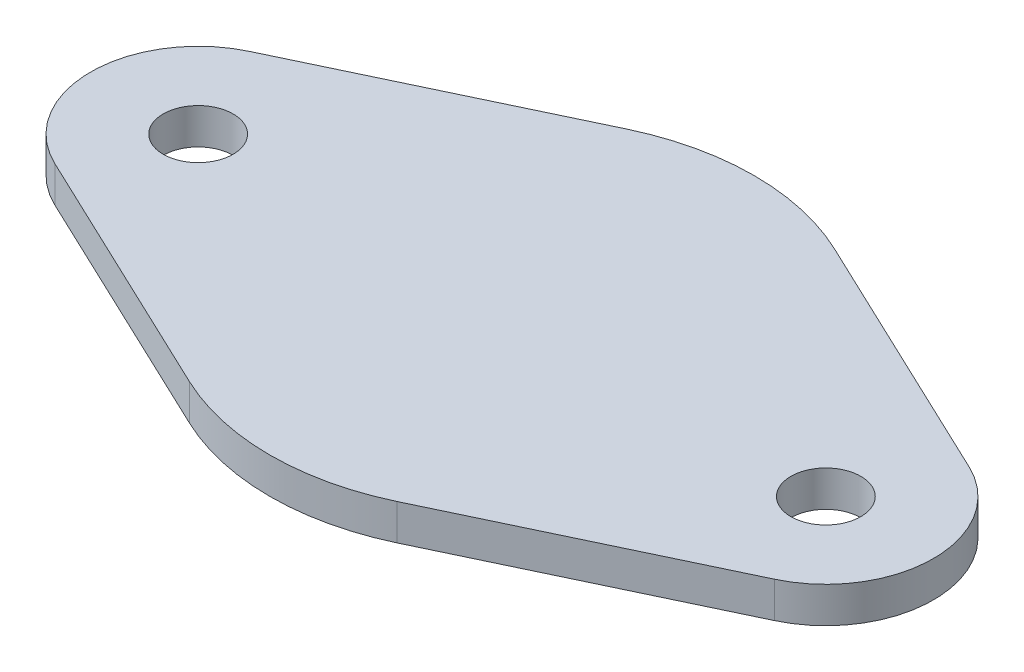
SolidWorks part; units mm, degrees
material "Thornel Mat VMA"
ref_plane "前视基准面" through (0, 0, 0) normal (0, 0, 1) x (1, 0, 0)
ref_plane "上视基准面" through (0, 0, 0) normal (0, 1, 0) x (1, 0, 0)
ref_plane "右视基准面" through (0, 0, 0) normal (1, 0, 0) x (0, 0, -1)
other "Configuration Table"
sketch "草图1" plane through (0, 0, 0) normal (0, 1, 0) x (1, 0, 0)
  line L0 (-40.5759, 0) -> (40.5265, 0) construction
  line L1 (0, 33.3733) -> (0, -29.1801) construction
  line L2 (-20.0714, 5.421) -> (-5.7857, 12.1974)
  line L3 (20.0714, 5.421) -> (5.7857, 12.1974)
  line L4 (20.0714, -5.421) -> (5.7857, -12.1974)
  line L5 (-20.0714, -5.421) -> (-5.7857, -12.1974)
  circle A0 centre (0, 0) radius 13.5 construction
  circle A1 centre (-17.5, 0) radius 1.95
  circle A2 centre (17.5, 0) radius 1.95
  arc A3 (-20.0714, 5.421) -> (-19.5517, -5.6383) centre (-17.5, 0) ccw
  arc A4 (20.0714, 5.421) -> (19.5517, -5.6383) centre (17.5, 0) cw
  arc A5 (5.7857, 12.1974) -> (-5.7857, 12.1974) centre (0, 0) ccw
  arc A6 (-5.7857, -12.1974) -> (5.7857, -12.1974) centre (0, 0) ccw
  point P17 (0, 0)
  point P23 (5.7675, -12.206)
  dimension "D1" = 27
  dimension "D2" = 35
  dimension "D3" = 3.9
  dimension "D4" = 6
extrude "凸台-拉伸1" add sketch "草图1" along normal blind 2
